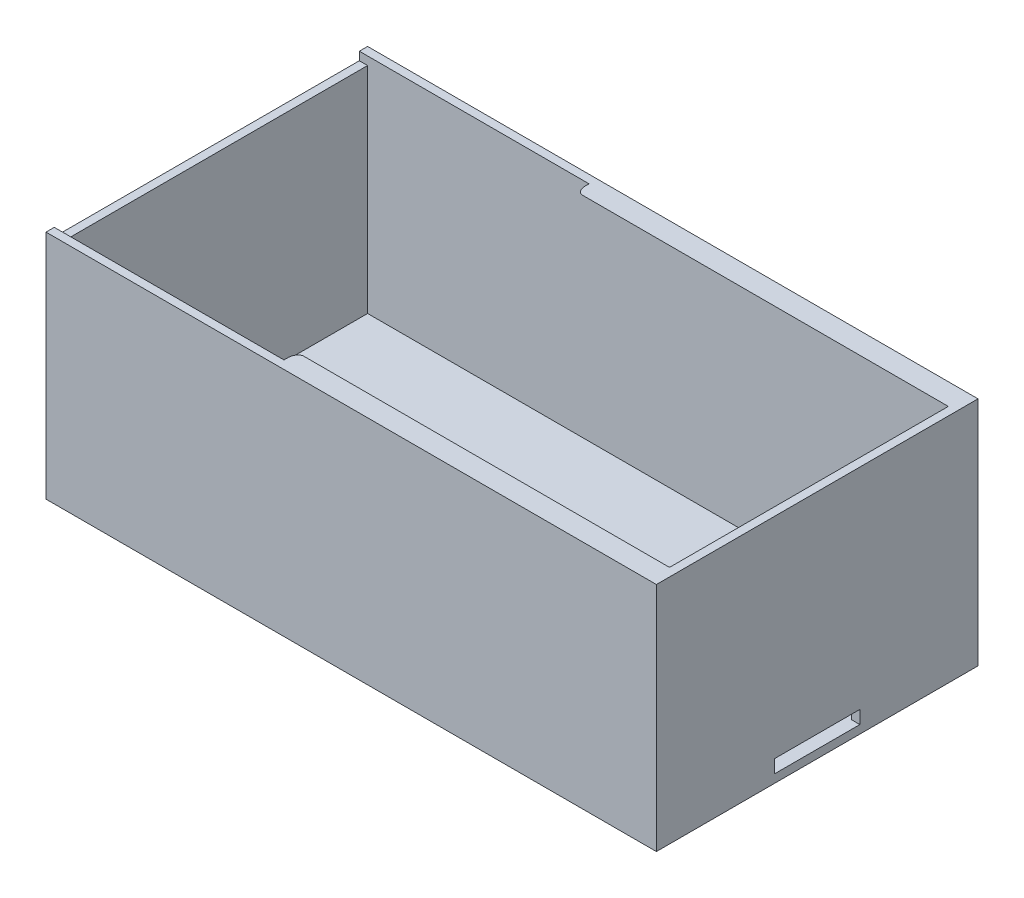
SolidWorks part; units mm, degrees
ref_plane "Plano frontal" through (0, 0, 0) normal (0, 0, 1) x (1, 0, 0)
ref_plane "Plano superior" through (0, 0, 0) normal (0, 1, 0) x (1, 0, 0)
ref_plane "Plano direito" through (0, 0, 0) normal (1, 0, 0) x (0, 0, -1)
sketch "Esboço1" plane through (0, 0, 0) normal (0, 1, 0) x (1, 0, 0)
  line L1 (0, 0) -> (93, 0)
  line L2 (0, 0) -> (0, -49)
  line L3 (0, -49) -> (93, -49)
  line L4 (93, 0) -> (93, -49)
  dimension "D1" = 93
  dimension "D2" = 49
extrude "Ressalto-extrusão1" add sketch "Esboço1" along normal blind 1.26
sketch "Esboço2" plane through (0, 0, 0) normal (0, 1, 0) x (1, 0, 0)
  line L0 (93, -49) -> (93, 0) construction
  line L1 (0, 0) -> (93, 0)
  line L2 (0, 0) -> (0, -1.26)
  line L3 (0, -1.26) -> (93, -1.26)
  line L4 (93, 0) -> (93, -1.26)
  line L6 (0, -49) -> (93, -49)
  line L7 (0, -49) -> (0, -47.74)
  line L8 (0, -47.74) -> (93, -47.74)
  line L9 (93, -49) -> (93, -47.74)
  dimension "D1" = 1.26
  dimension "D2" = 1.26
extrude "Ressalto-extrusão2" add sketch "Esboço2" along normal blind 35.24
sketch "Esboço3" plane through (0, 0, 0) normal (0, 1, 0) x (1, 0, 0)
  line L0 (0, -49) -> (93, -49) construction
  line L1 (93, 0) -> (91.74, 0)
  line L2 (93, 0) -> (93, -49)
  line L3 (93, -49) -> (91.74, -49)
  line L4 (91.74, 0) -> (91.74, -49)
  dimension "D1" = 1.26
extrude "Ressalto-extrusão4" add sketch "Esboço3" along normal blind 35.24
sketch "Esboço5" plane through (0, 0, 0) normal (1, 0, 0) x (0, 0, -1)
  line L0 (0, 35.24) -> (-3.26, 35.24)
  line L1 (-1.26, 35.24) -> (-47.74, 35.24) construction
  line L2 (-3.26, 35.24) -> (0, 31.98)
  line L4 (-49, 35.24) -> (-45.74, 35.24)
  line L5 (-45.74, 35.24) -> (-49, 31.98)
  line L6 (-49, 35.24) -> (-49, 0) construction
  line L7 (-49, 31.98) -> (-49, 35.24)
  line L8 (0, 35.24) -> (0, 0) construction
  line L9 (0, 31.98) -> (0, 35.24)
  dimension "D1" = 3.26
  dimension "D2" = 3.26
extrude "Ressalto-extrusão5" add sketch "Esboço5" along normal blind 57 from offset 35
fillet "Filete1" radius 1 1 edges at (35, 34.24, 46.74)
fillet "Filete2" radius 1 1 edges at (35, 34.24, 2.26)
sketch "Esboço6" plane through (0, 0, 0) normal (0, 1, 0) x (1, 0, 0)
  line L0 (0, -49) -> (93, -49) construction
  line L1 (0, 0) -> (1.26, 0)
  line L2 (0, 0) -> (0, -49)
  line L3 (0, -49) -> (1.26, -49)
  line L4 (1.26, 0) -> (1.26, -49)
  dimension "D1" = 1.26
extrude "Ressalto-extrusão6" add sketch "Esboço6" along normal blind 33.98
sketch "Esboço7" plane through (0, 0, 0) normal (-1, 0, 0) x (0, 0, 1)
  line L0 (0, 0) -> (49, 0) construction
  line L1 (19, 3.26) -> (30, 3.26)
  line L2 (19, 3.26) -> (19, 1.26)
  line L3 (19, 1.26) -> (30, 1.26)
  line L4 (30, 3.26) -> (30, 1.26)
  line L5 (0, 35.24) -> (0, 0) construction
  dimension "D1" = 1.26
  dimension "D2" = 2
  dimension "D3" = 19
  dimension "D4" = 11
extrude "Corte-extrusão1" cut sketch "Esboço7" against normal blind 1.26
sketch "Esboço8" plane through (93, 0, 0) normal (1, 0, 0) x (0, 0, -1)
  line L0 (-49, 0) -> (0, 0) construction
  line L1 (-31, 3.26) -> (-18, 3.26)
  line L2 (-31, 3.26) -> (-31, 1.26)
  line L3 (-31, 1.26) -> (-18, 1.26)
  line L4 (-18, 3.26) -> (-18, 1.26)
  line L5 (-49, 35.24) -> (-49, 0) construction
  dimension "D1" = 13
  dimension "D2" = 2
  dimension "D3" = 1.26
  dimension "D4" = 18
extrude "Corte-extrusão2" cut sketch "Esboço8" against normal blind 1.26
sketch "Esboço10" plane through (0, 1.26, 0) normal (0, 1, 0) x (1, 0, 0)
  line L0 (4, -15.74) -> (4, -17)
  line L1 (4, -17) -> (8, -17)
  line L2 (8, -17) -> (8, -19)
  line L3 (8, -19) -> (9.26, -19)
  line L4 (9.26, -19) -> (9.26, -15.74)
  line L5 (9.26, -15.74) -> (4, -15.74)
  line L6 (4, -32) -> (4, -33.26)
  line L7 (4, -33.26) -> (9.26, -33.26)
  line L8 (9.26, -33.26) -> (9.26, -30)
  line L9 (9.26, -30) -> (8, -30)
  line L10 (8, -30) -> (8, -32)
  line L11 (8, -32) -> (4, -32)
  line L12 (1.26, -47.74) -> (91.74, -47.74) construction
  line L13 (0, -1.26) -> (0, -47.74) construction
  line L15 (0, -49) -> (93, -49) construction
  dimension "D1" = 1.26
  dimension "D2" = 1.26
  dimension "D3" = 1.26
  dimension "D4" = 1.26
  dimension "D5" = 8
  dimension "D6" = 8
  dimension "D7" = 15
  dimension "D8" = 2
  dimension "D9" = 2
  dimension "D10" = 17
  dimension "D11" = 4
extrude "Ressalto-extrusão7" add sketch "Esboço10" along normal blind 2
sketch "Esboço11" plane through (0, 1.26, 0) normal (0, 1, 0) x (1, 0, 0)
  line L0 (87.74, -14.24) -> (83.74, -14.24)
  line L1 (83.74, -14.24) -> (83.74, -17.5)
  line L2 (83.74, -17.5) -> (85, -17.5)
  line L3 (85, -17.5) -> (85, -15.5)
  line L4 (85, -15.5) -> (87.74, -15.5)
  line L5 (87.74, -15.5) -> (87.74, -14.24)
  line L6 (87.74, -33.5) -> (87.74, -34.76)
  line L7 (87.74, -34.76) -> (83.74, -34.76)
  line L8 (83.74, -34.76) -> (83.74, -31.5)
  line L9 (83.74, -31.5) -> (85, -31.5)
  line L10 (85, -31.5) -> (85, -33.5)
  line L11 (85, -33.5) -> (87.74, -33.5)
  line L12 (91.74, -47.74) -> (91.74, -31) construction
  line L13 (93, -49) -> (93, 0) construction
  line L14 (0, -49) -> (93, -49) construction
  dimension "D1" = 1.26
  dimension "D2" = 1.26
  dimension "D3" = 4
  dimension "D4" = 8
  dimension "D5" = 18
  dimension "D6" = 15.5
  dimension "D7" = 2
extrude "Ressalto-extrusão8" add sketch "Esboço11" along normal blind 2
